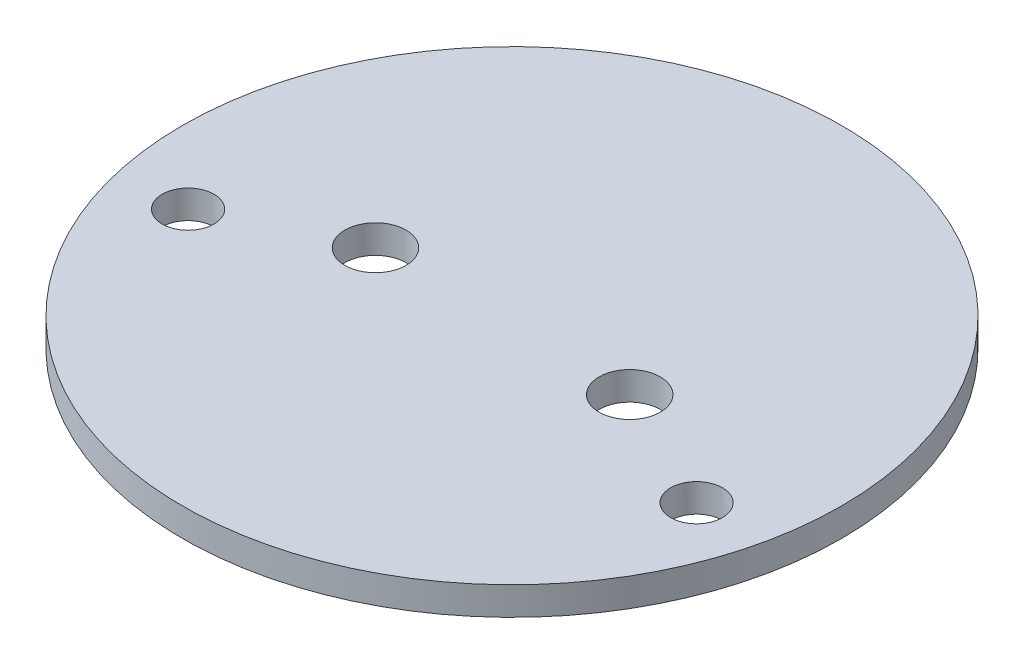
SolidWorks part; units mm, degrees
material "A-Glass Fiber"
ref_plane "Front Plane" through (0, 0, 0) normal (0, 0, 1) x (1, 0, 0)
ref_plane "Top Plane" through (0, 0, 0) normal (0, 1, 0) x (1, 0, 0)
ref_plane "Right Plane" through (0, 0, 0) normal (1, 0, 0) x (0, 0, -1)
sketch "Sketch2" plane through (0, 0, 0) normal (0, 0, 1) x (1, 0, 0)
  line L0 (0, -417.1122) -> (0, 20438.4966) construction
  line L1 (0, 0) -> (35, 0)
  line L2 (35, 0) -> (35, 3)
  line L5 (35, 3) -> (0, 3)
  line L6 (0, 3) -> (0, 0)
  point P5 (35, 5)
  point P7 (34.6747, 5)
  dimension "D1" = 3
  dimension "D4" = 70
revolve "Revolve1" add sketch "Sketch2" angle 360 about L0
sketch "Sketch3" plane through (0, 3, 0) normal (0, 1, 0) x (1, 0, 0)
  line L0 (-13.5, -1) -> (13.5, -1) construction
  circle A0 centre (-13.5, -1) radius 3.25
  circle A1 centre (13.5, -1) radius 3.25
  point P4 (0, -1)
  dimension "D1" = 6.5
  dimension "D2" = 27
  dimension "D3" = 1
extrude "Cut-Extrude1" cut sketch "Sketch3" against normal up to next
sketch "Sketch4" plane through (0, 3, 0) normal (0, 1, 0) x (1, 0, 0)
  line L0 (-27, -7.4) -> (27, -7.4) construction
  circle A0 centre (-27, -7.4) radius 2.75
  circle A1 centre (27, -7.4) radius 2.75
  point P4 (0, -7.4)
  dimension "D3" = 5.5
  dimension "D1" = 54
  dimension "D2" = 7.4
extrude "Cut-Extrude2" cut sketch "Sketch4" against normal up to next
